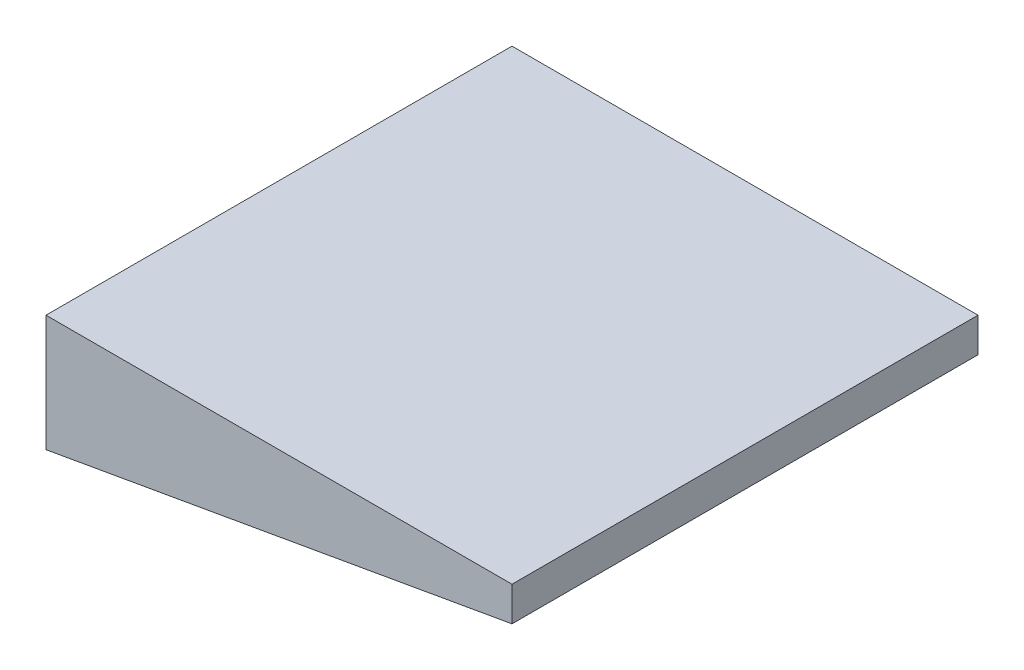
SolidWorks part; units mm, degrees
ref_plane "Front Plane" through (0, 0, 0) normal (0, 0, 1) x (1, 0, 0)
ref_plane "Top Plane" through (0, 0, 0) normal (0, 1, 0) x (1, 0, 0)
ref_plane "Right Plane" through (0, 0, 0) normal (1, 0, 0) x (0, 0, -1)
sketch "Sketch1" plane through (0, 0, 0) normal (0, 1, 0) x (1, 0, 0)
  line L1 (-3.175, -3.175) -> (3.175, -3.175)
  line L2 (-3.175, -3.175) -> (-3.175, 3.175)
  line L3 (-3.175, 3.175) -> (3.175, 3.175)
  line L4 (3.175, -3.175) -> (3.175, 3.175)
  line L5 (-3.175, -3.175) -> (3.175, 3.175) construction
  line L6 (-3.175, 3.175) -> (3.175, -3.175) construction
  point P0 (0, 0)
  dimension "D1" = 6.35
  dimension "D2" = 6.35
extrude "Boss-Extrude1" add sketch "Sketch1" along normal blind 1.5875
sketch "Sketch2" plane through (0, 0, 3.175) normal (0, 0, 1) x (1, 0, 0)
  line L0 (-3.175, 0) -> (3.175, 1.1197)
  line L1 (-3.175, 0) -> (3.175, 0) construction
  line L2 (3.175, 1.5875) -> (3.175, 0) construction
  line L3 (3.175, 1.1197) -> (3.175, 0)
  line L4 (3.175, 0) -> (-3.175, 0)
  dimension "D1" = 0
  dimension "D2" = 80
extrude "Cut-Extrude1" cut sketch "Sketch2" against normal through all
